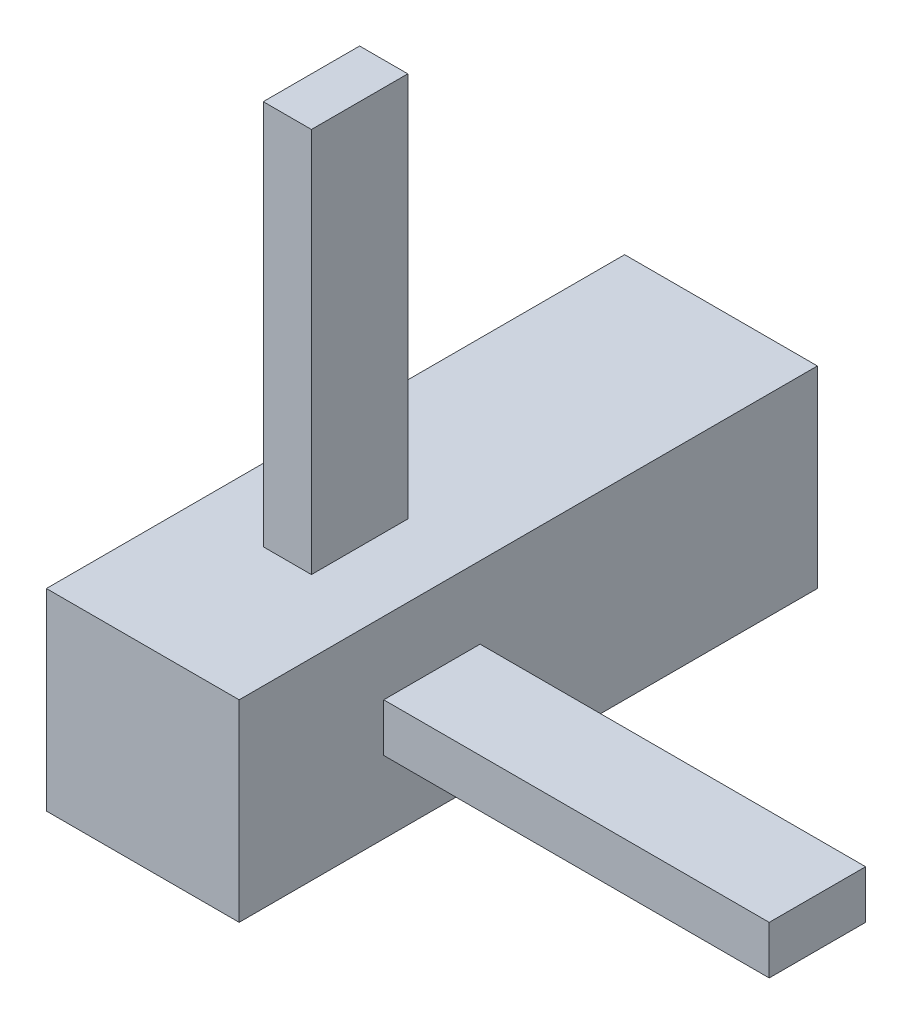
SolidWorks part; units mm, degrees
ref_plane "Front Plane" through (0, 0, 0) normal (0, 0, 1) x (1, 0, 0)
ref_plane "Top Plane" through (0, 0, 0) normal (0, 1, 0) x (1, 0, 0)
ref_plane "Right Plane" through (0, 0, 0) normal (1, 0, 0) x (0, 0, -1)
sketch "Sketch2" plane through (0, 0, 0) normal (0, 0, 1) x (1, 0, 0)
  line L5 (-0.1, -0.1) -> (0.1, -0.1)
  line L6 (-0.1, -0.1) -> (-0.1, 0.1)
  line L7 (-0.1, 0.1) -> (0.1, 0.1)
  line L8 (0.1, -0.1) -> (0.1, 0.1)
  line L9 (-0.1, -0.1) -> (0.1, 0.1) construction
  line L10 (-0.1, 0.1) -> (0.1, -0.1) construction
  point P0 (0, 0)
  dimension "D1" = 0.2
extrude "Boss-Extrude1" add sketch "Sketch2" along normal blind 0.6
sketch "Sketch3" plane through (0.1, 0, 0) normal (1, 0, 0) x (0, 0, -1)
  line L1 (-0.45, -0.025) -> (-0.35, -0.025)
  line L2 (-0.45, -0.025) -> (-0.45, 0.025)
  line L3 (-0.45, 0.025) -> (-0.35, 0.025)
  line L4 (-0.35, -0.025) -> (-0.35, 0.025)
  line L5 (-0.45, -0.025) -> (-0.35, 0.025) construction
  line L6 (-0.45, 0.025) -> (-0.35, -0.025) construction
  point P0 (-0.4, 0)
  point P5 (0, 0)
  dimension "D1" = 0.4
  dimension "D2" = 0.1
  dimension "D3" = 0.05
extrude "Boss-Extrude2" add sketch "Sketch3" along normal blind 0.4
ref_plane "Plane1" through (0, 0, 0) normal (-0.7071, 0.7071, 0) x (0.7071, 0.7071, 0)
mirror "Mirror1" about plane through (0, 0, 0) normal (-0.7071, 0.7071, 0) of "Boss-Extrude2"
